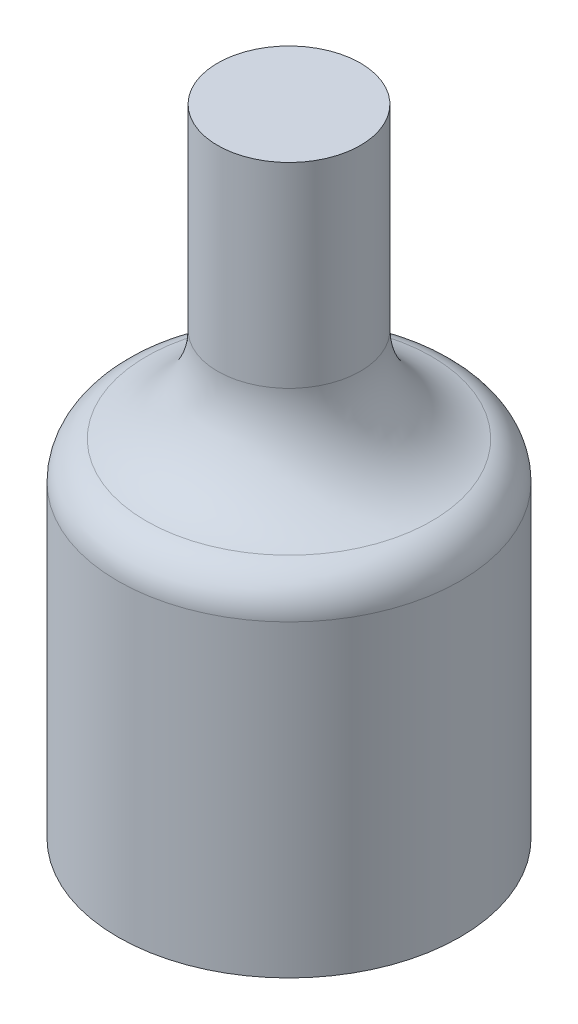
SolidWorks part; units mm, degrees
ref_plane "Front Plane" through (0, 0, 0) normal (0, 0, 1) x (1, 0, 0)
ref_plane "Top Plane" through (0, 0, 0) normal (0, 1, 0) x (1, 0, 0)
ref_plane "Right Plane" through (0, 0, 0) normal (1, 0, 0) x (0, 0, -1)
sketch "Sketch1" plane through (0, 0, 0) normal (0, 0, 1) x (1, 0, 0)
  line L0 (0, 0) -> (0, 23.9176) construction
  line L1 (0, 41.275) -> (4.6355, 41.275)
  line L2 (4.6355, 41.275) -> (4.6355, 22.225)
  line L3 (4.6355, 22.225) -> (11.1125, 22.225)
  line L4 (11.1125, 22.225) -> (11.1125, 0)
  line L5 (11.1125, 0) -> (0, 0)
  line L6 (0, 41.275) -> (0, 0)
  dimension "D1" = 9.271
  dimension "D2" = 22.225
  dimension "D3" = 22.225
  dimension "D4" = 19.05
revolve "Revolve1" add sketch "Sketch1" angle 360 about L0
sketch "Sketch2" plane through (0, 0, 0) normal (0, -1, 0) x (1, 0, 0)
  line L1 (6.604, 3.8128) -> (0, 7.6256)
  line L2 (0, 7.6256) -> (-6.604, 3.8128)
  line L3 (-6.604, 3.8128) -> (-6.604, -3.8128)
  line L4 (-6.604, -3.8128) -> (0, -7.6256)
  line L5 (0, -7.6256) -> (6.604, -3.8128)
  line L6 (6.604, -3.8128) -> (6.604, 3.8128)
  circle A0 centre (0, 0) radius 6.604 construction
  point P1 (0, 0)
  dimension "D1" = 13.208
extrude "Cut-Extrude1" cut sketch "Sketch2" against normal blind 15.875
fillet "Fillet1" radius 6.35 1 edges at (0, 22.225, -4.6355)
fillet "Fillet2" radius 2.54 1 edges at (0, 22.225, -11.1125)
